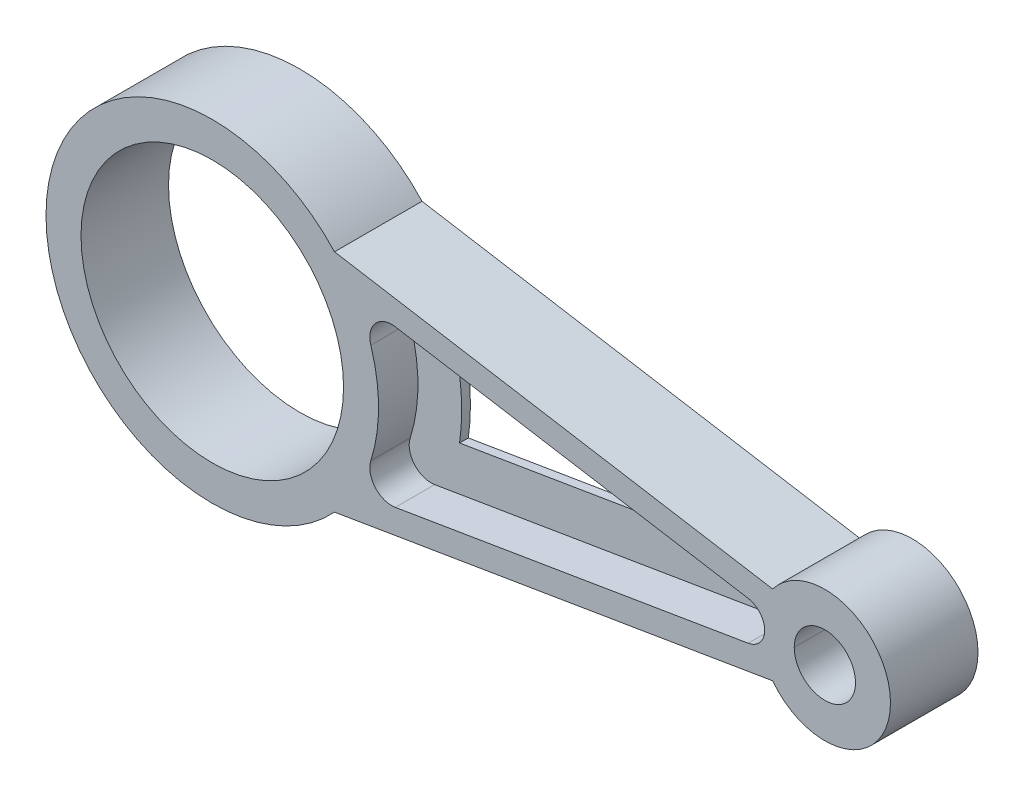
SolidWorks part; units mm, degrees
material "Plain Carbon Steel"
ref_plane "Front Plane" through (0, 0, 0) normal (0, 0, 1) x (1, 0, 0)
ref_plane "Top Plane" through (0, 0, 0) normal (0, 1, 0) x (1, 0, 0)
ref_plane "Right Plane" through (0, 0, 0) normal (1, 0, 0) x (0, 0, -1)
sketch "Sketch1" plane through (0, 0, 0) normal (0, 0, 1) x (1, 0, 0)
  line L0 (-102.3917, 0) -> (200.7225, 0) construction
  line L1 (27.9355, 25.7606) -> (128.0638, 9.0844)
  line L2 (27.9355, -25.7606) -> (128.0638, -9.0844)
  circle A0 centre (0, 0) radius 30
  arc A1 (27.9355, 25.7606) -> (27.9355, -25.7606) centre (0, 0) ccw
  circle A2 centre (140, 0) radius 7
  arc A3 (128.0638, -9.0844) -> (128.0638, 9.0844) centre (140, 0) ccw
  point P13 (23.8155, 30)
  dimension "D2" = 60
  dimension "D3" = 76
  dimension "D4" = 30
  dimension "D5" = 14
  dimension "D1" = 140
extrude "Boss-Extrude1" add sketch "Sketch1" along normal mid plane 20
sketch "Sketch2" plane through (0, 0, 10) normal (0, 0, 1) x (1, 0, 0)
  line L0 (0, 0) -> (213.9156, 0) construction
  line L1 (41.8286, 17.871) -> (122.4784, 4.4389)
  line L2 (122.4784, -4.4389) -> (41.8286, -17.871)
  line L3 (128.0638, 9.0844) -> (27.9355, 25.7606) construction
  arc A0 (36.2389, -11.4344) -> (36.2389, 11.4344) centre (0, 0) ccw
  circle A1 centre (0, 0) radius 30 construction
  arc A3 (36.2389, -11.4344) -> (41.8286, -17.871) centre (41.0071, -12.9389) ccw
  arc A4 (36.2389, 11.4344) -> (41.8286, 17.871) centre (41.0071, 12.9389) cw
  arc A5 (122.4784, 4.4389) -> (122.4784, -4.4389) centre (121.7391, 0) cw
  point P10 (0, 0)
  dimension "D1" = 8
  dimension "D3" = 4.5
  dimension "D4" = 5
  dimension "D2" = 5.5
extrude "Cut-Extrude1" cut sketch "Sketch2" against normal blind 9
mirror "Mirror1" about plane through (0, 0, 0) normal (0, 0, 1) of "Cut-Extrude1"
split line "Split Line1"
sketch "Sketch3" plane through (0, 0, 1) normal (0, 0, 1) x (1, 0, 0)
  line L0 (41.8286, -17.871) -> (122.4784, -4.4389) construction
  line L1 (122.4784, 4.4389) -> (41.8286, 17.871) construction
  line L2 (41.8286, -17.871) -> (122.4784, -4.4389)
  line L3 (122.4784, 4.4389) -> (41.8286, 17.871)
  line L4 (88.2609, 0) -> (47.5179, 6.7857)
  line L5 (47.5179, -6.7857) -> (88.2609, 0)
  arc A0 (122.4784, -4.4389) -> (122.4784, 4.4389) centre (121.7391, 0) ccw construction
  arc A1 (36.2389, -11.4344) -> (41.8286, -17.871) centre (41.0071, -12.9389) ccw construction
  arc A2 (36.2389, -11.4344) -> (36.2389, 11.4344) centre (0, 0) ccw construction
  arc A3 (41.8286, 17.871) -> (36.2389, 11.4344) centre (41.0071, 12.9389) ccw construction
  arc A4 (122.4784, -4.4389) -> (122.4784, 4.4389) centre (121.7391, 0) ccw
  arc A5 (36.2389, -11.4344) -> (41.8286, -17.871) centre (41.0071, -12.9389) ccw
  arc A6 (36.2389, -11.4344) -> (36.2389, 11.4344) centre (0, 0) ccw
  arc A7 (41.8286, 17.871) -> (36.2389, 11.4344) centre (41.0071, 12.9389) ccw
  arc A8 (47.5179, 6.7857) -> (47.5179, 6.7857) centre (47.5179, 6.7857) ccw
  arc A9 (47.5179, -6.7857) -> (47.5179, 6.7857) centre (0, 0) ccw
  arc A10 (47.5179, -6.7857) -> (47.5179, -6.7857) centre (47.5179, -6.7857) ccw
  arc A11 (88.2609, 0) -> (88.2609, 0) centre (88.2609, 0) ccw
  dimension "D1" = 10
extrude "Cut-Extrude2" cut sketch "Sketch3" against normal through all contours A9 L5 L4
